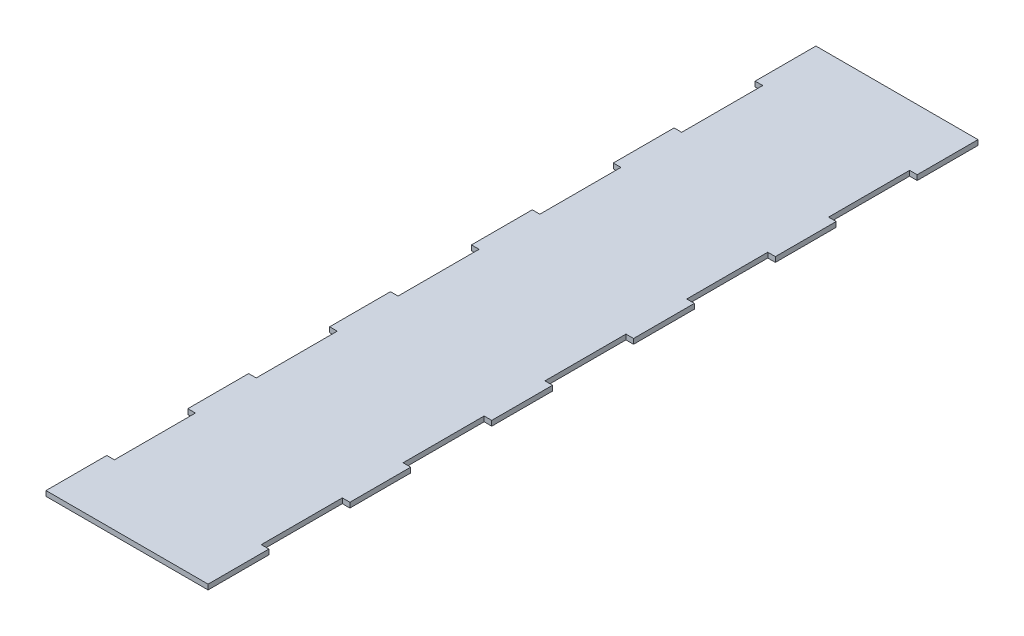
SolidWorks part; units mm, degrees
ref_plane "Front Plane" through (0, 0, 0) normal (0, 0, 1) x (1, 0, 0)
ref_plane "Top Plane" through (0, 0, 0) normal (0, 1, 0) x (1, 0, 0)
ref_plane "Right Plane" through (0, 0, 0) normal (1, 0, 0) x (0, 0, -1)
sketch "Sketch1" plane through (0, 0, 0) normal (0, 1, 0) x (1, 0, 0)
  line L0 (-50.8, 0) -> (50.8, 0)
  line L1 (-50.8, 0) -> (-50.8, 38.1)
  line L2 (-50.8, 38.1) -> (-46.0375, 38.1)
  line L3 (-46.0375, 38.1) -> (-46.0375, 88.9)
  line L4 (-46.0375, 88.9) -> (-50.8, 88.9)
  line L5 (-50.8, 88.9) -> (-50.8, 127)
  line L6 (-50.8, 127) -> (-46.0375, 127)
  line L7 (-46.0375, 127) -> (-46.0375, 177.8)
  line L8 (-46.0375, 177.8) -> (-50.8, 177.8)
  line L9 (-50.8, 177.8) -> (-50.8, 215.9)
  line L10 (-50.8, 215.9) -> (-46.0375, 215.9)
  line L11 (-46.0375, 215.9) -> (-46.0375, 266.7)
  line L12 (-46.0375, 266.7) -> (-50.8, 266.7)
  line L13 (-50.8, 266.7) -> (-50.8, 304.8)
  line L14 (-50.8, 304.8) -> (-46.0375, 304.8)
  line L15 (0, -1000) -> (0, 49000) construction
  line L16 (-46.0375, 304.8) -> (-46.0375, 355.6)
  line L17 (-46.0375, 355.6) -> (-50.8, 355.6)
  line L18 (-50.8, 355.6) -> (-50.8, 393.7)
  line L19 (-50.8, 393.7) -> (-46.0375, 393.7)
  line L20 (-46.0375, 393.7) -> (-46.0375, 444.5)
  line L21 (-46.0375, 444.5) -> (-50.8, 444.5)
  line L22 (-50.8, 444.5) -> (-50.8, 482.6)
  line L23 (-50.8, 482.6) -> (50.8, 482.6)
  line L24 (50.8, 444.5) -> (50.8, 482.6)
  line L25 (46.0375, 444.5) -> (50.8, 444.5)
  line L26 (46.0375, 393.7) -> (46.0375, 444.5)
  line L27 (50.8, 393.7) -> (46.0375, 393.7)
  line L28 (50.8, 355.6) -> (50.8, 393.7)
  line L29 (46.0375, 355.6) -> (50.8, 355.6)
  line L30 (46.0375, 304.8) -> (46.0375, 355.6)
  line L31 (50.8, 304.8) -> (46.0375, 304.8)
  line L32 (50.8, 266.7) -> (50.8, 304.8)
  line L33 (46.0375, 266.7) -> (50.8, 266.7)
  line L34 (46.0375, 215.9) -> (46.0375, 266.7)
  line L35 (50.8, 215.9) -> (46.0375, 215.9)
  line L36 (50.8, 177.8) -> (50.8, 215.9)
  line L37 (46.0375, 177.8) -> (50.8, 177.8)
  line L38 (46.0375, 127) -> (46.0375, 177.8)
  line L39 (50.8, 127) -> (46.0375, 127)
  line L40 (50.8, 88.9) -> (50.8, 127)
  line L41 (46.0375, 88.9) -> (50.8, 88.9)
  line L42 (46.0375, 38.1) -> (46.0375, 88.9)
  line L43 (50.8, 38.1) -> (46.0375, 38.1)
  line L44 (50.8, 0) -> (50.8, 38.1)
  point P14 (0, 482.6)
  point P33 (0, 0)
  point P50 (0, 0)
  dimension "D1" = 50.8
  dimension "D2" = 38.1
  dimension "D3" = 50.8
  dimension "D4" = 4.7625
  dimension "D6" = 38.1
  dimension "D5" = 5
extrude "Boss-Extrude1" add sketch "Sketch1" along normal blind 3.175
